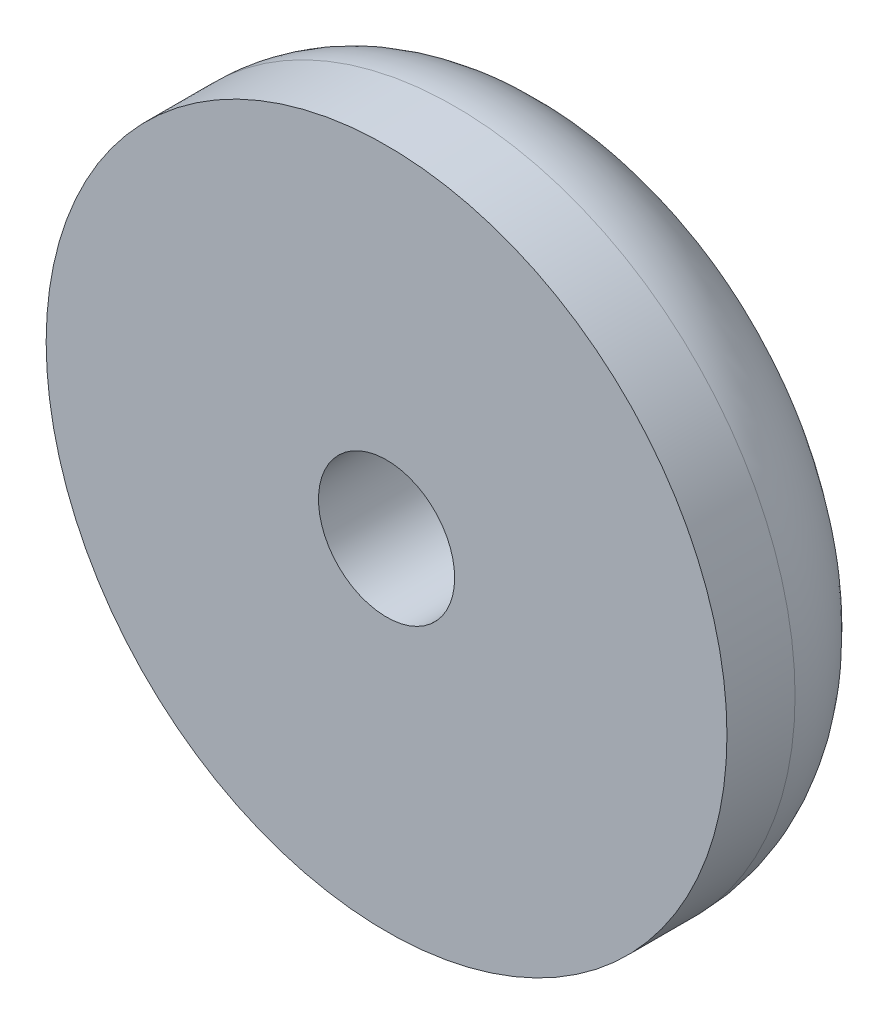
SolidWorks part; units mm, degrees
ref_plane "Front Plane" through (0, 0, 0) normal (0, 0, 1) x (1, 0, 0)
ref_plane "Top Plane" through (0, 0, 0) normal (0, 1, 0) x (1, 0, 0)
ref_plane "Right Plane" through (0, 0, 0) normal (1, 0, 0) x (0, 0, -1)
sketch "Sketch1" plane through (0, 0, 0) normal (0, 0, 1) x (1, 0, 0)
  circle A0 centre (0, 0) radius 7.5
  circle A1 centre (0, 0) radius 1.5
  dimension "D1" = 15
  dimension "D2" = 3
extrude "Boss-Extrude1" add sketch "Sketch1" along normal blind 4
fillet "Fillet1" radius 2.5 1 edges at (7.5, 0, 0)
